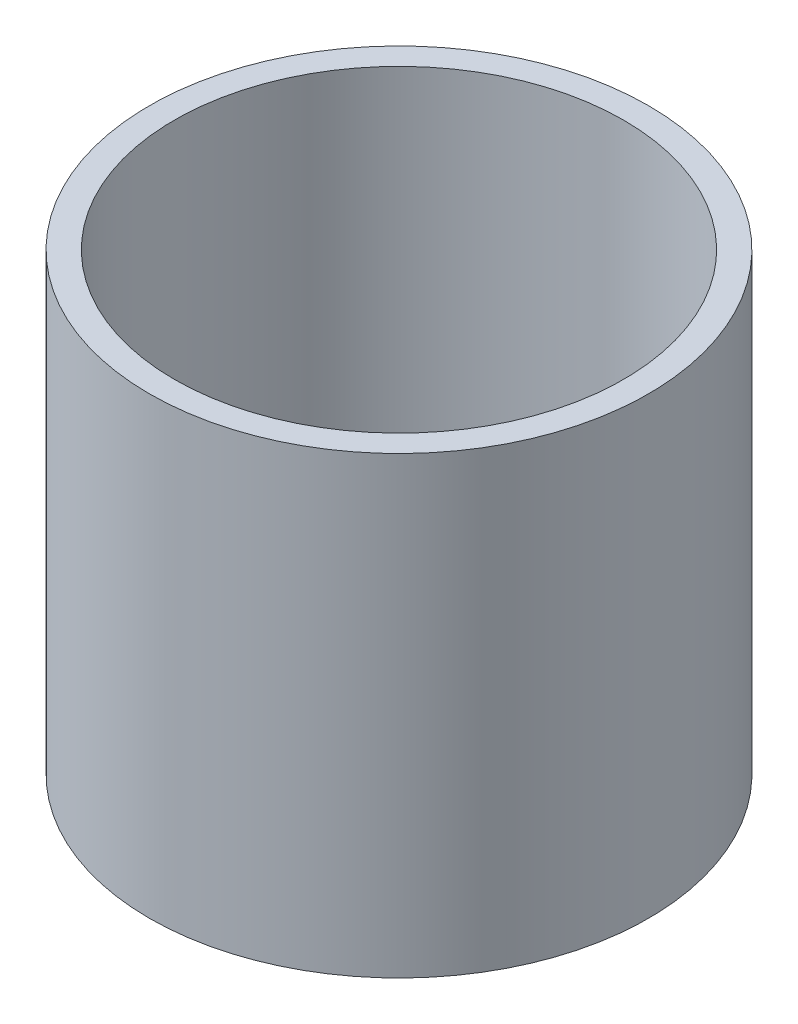
SolidWorks part; units mm, degrees
ref_plane "Front Plane" through (0, 0, 0) normal (0, 0, 1) x (1, 0, 0)
ref_plane "Top Plane" through (0, 0, 0) normal (0, 1, 0) x (1, 0, 0)
ref_plane "Right Plane" through (0, 0, 0) normal (1, 0, 0) x (0, 0, -1)
sketch "Sketch1" plane through (0, 0, 0) normal (0, 1, 0) x (1, 0, 0)
  circle A0 centre (0, 0) radius 50
extrude "Boss-Extrude1" add sketch "Sketch1" along normal blind 13
sketch "Sketch2" plane through (0, 13, 0) normal (0, 1, 0) x (1, 0, 0)
  line L0 (-35.0151, 35.7978) -> (34.9849, 35.7978)
  line L1 (34.9849, 35.7978) -> (34.9849, -19.2022)
  line L2 (34.9849, -19.2022) -> (-35.0151, -19.2022)
  line L3 (-35.0151, -19.2022) -> (-35.0151, 35.7978)
extrude "Cut-Extrude1" cut sketch "Sketch2" against normal blind 10 contours L3 L0 L1 L2
sketch "Sketch3" plane through (0, 13, 0) normal (0, 1, 0) x (1, 0, 0)
  line L0 (-35.0151, 35.6923) -> (34.9849, 35.722)
  arc A0 (-35.0151, 35.6923) -> (34.9849, 35.722) centre (0, 0) cw
extrude "Cut-Extrude3" cut sketch "Sketch3" against normal blind 10
sketch "Sketch6" plane through (0, 13, 0) normal (0, 1, 0) x (1, 0, 0)
  circle A0 centre (0, 0) radius 50
  circle A1 centre (0, 0) radius 50
  circle A2 centre (0, 0) radius 50
extrude "Boss-Extrude5" add sketch "Sketch6" along normal blind 3 contours A0
sketch "Sketch11" plane through (0, 16, 0) normal (0, 1, 0) x (1, 0, 0)
  line L0 (-20, 45.8258) -> (20, 45.8258)
  line L1 (20, 45.8258) -> (20, -19.1742)
  line L2 (20, -19.1742) -> (-20, -19.1742)
  line L3 (-20, -19.1742) -> (-20, 45.8258)
  circle A0 centre (0, 0) radius 50 construction
extrude "Cut-Extrude12" cut sketch "Sketch11" against normal blind 10
sketch "Sketch12" plane through (0, 16, 0) normal (0, 1, 0) x (1, 0, 0)
  line L0 (-20, 45.8258) -> (20, 45.8258)
  arc A0 (-20, 45.8258) -> (20, 45.8258) centre (0, 0) cw
extrude "Cut-Extrude13" cut sketch "Sketch12" against normal blind 10
sketch "Sketch13" plane through (0, 16, 0) normal (0, 1, 0) x (1, 0, 0)
  circle A0 centre (0, 0) radius 50
extrude "Boss-Extrude6" add sketch "Sketch13" along normal blind 75
sketch "Sketch14" plane through (0, 91, 0) normal (0, 1, 0) x (1, 0, 0)
  circle A0 centre (0, 0) radius 45
extrude "Cut-Extrude14" cut sketch "Sketch14" against normal blind 75
